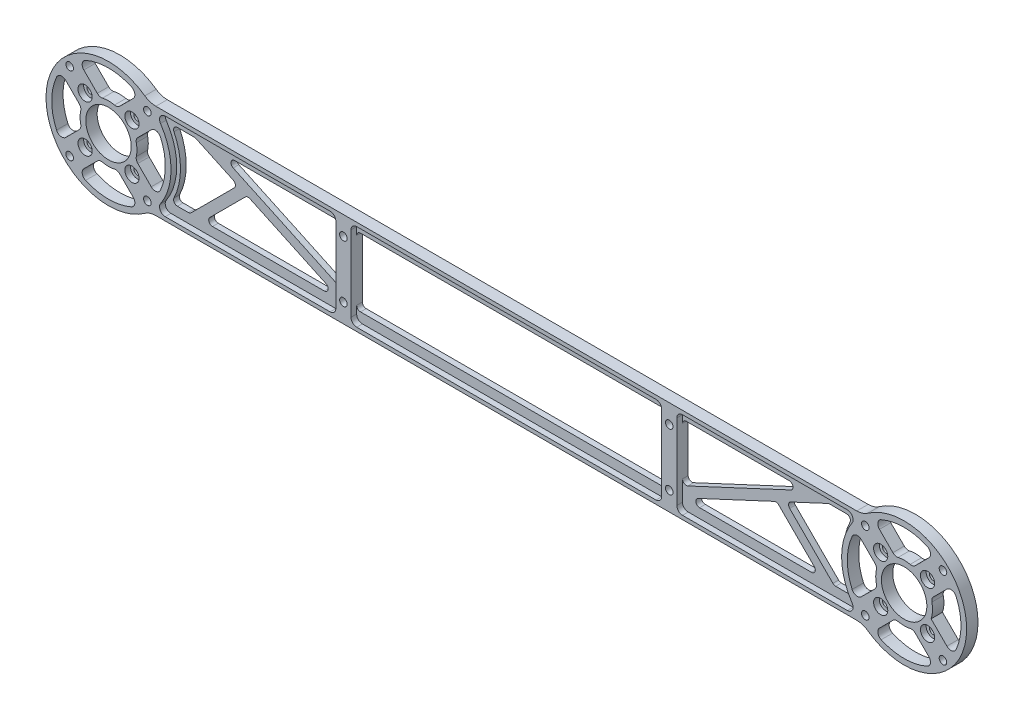
SolidWorks part; units mm, degrees
material "6061 合金"
ref_plane "前视基准面" through (0, 0, 0) normal (0, 0, 1) x (1, 0, 0)
ref_plane "上视基准面" through (0, 0, 0) normal (0, 1, 0) x (1, 0, 0)
ref_plane "右视基准面" through (0, 0, 0) normal (1, 0, 0) x (0, 0, -1)
sketch "草图1" plane through (0, 0, 0) normal (0, 0, 1) x (1, 0, 0)
  line L0 (0, 45.7031) -> (0, -72.9118) construction
  line L1 (-42.6422, 0) -> (420, 0) construction
  line L2 (0, 0) -> (-20.5061, 20.5061) construction
  line L3 (21.5407, 25) -> (398.4593, 25)
  line L4 (21.5407, -25) -> (398.4593, -25)
  line L5 (210, 25) -> (210, -95.809) construction
  line L7 (30.0167, 18) -> (120, 18)
  line L8 (30.0167, 18) -> (30.0167, -18) construction
  line L9 (30.0167, -18) -> (120, -18)
  line L10 (120, 18) -> (120, -18)
  line L11 (30.0167, 18) -> (120, -18) construction
  line L12 (30.0167, -18) -> (120, 18) construction
  line L13 (300, 18) -> (389.9833, 18)
  line L14 (300, 18) -> (300, -18)
  line L15 (300, -18) -> (389.9833, -18)
  line L16 (389.9833, 18) -> (389.9833, -18) construction
  line L17 (300, 18) -> (389.9833, -18) construction
  line L18 (300, -18) -> (389.9833, 18) construction
  line L19 (128, 18) -> (292, 18)
  line L20 (128, 18) -> (128, -18)
  line L21 (128, -18) -> (292, -18)
  line L22 (292, 18) -> (292, -18)
  line L23 (128, 18) -> (292, -18) construction
  line L24 (128, -18) -> (292, 18) construction
  circle A0 centre (0, 0) radius 29 construction
  circle A1 centre (-20.5061, 20.5061) radius 2
  circle A5 centre (20.5061, 20.5061) radius 2
  circle A6 centre (20.5061, -20.5061) radius 2
  circle A7 centre (-20.5061, -20.5061) radius 2
  circle A8 centre (0, 0) radius 12
  arc A9 (21.5407, 25) -> (21.5407, -25) centre (0, 0) ccw
  circle A10 centre (440.5061, 20.5061) radius 2
  arc A11 (398.4593, -25) -> (398.4593, 25) centre (420, 0) ccw
  circle A12 centre (420, 0) radius 12
  circle A13 centre (440.5061, -20.5061) radius 2
  circle A14 centre (399.4939, -20.5061) radius 2
  circle A15 centre (399.4939, 20.5061) radius 2
  arc A17 (389.9833, 18) -> (389.9833, -18) centre (420, 0) ccw
  arc A18 (30.0167, -18) -> (30.0167, 18) centre (0, 0) ccw
  circle A19 centre (-12.3744, 12.3744) radius 2
  circle A20 centre (12.3744, 12.3744) radius 2
  circle A21 centre (12.3744, -12.3744) radius 2
  circle A22 centre (-12.3744, -12.3744) radius 2
  circle A23 centre (407.6256, 12.3744) radius 2
  circle A24 centre (432.3744, 12.3744) radius 2
  circle A25 centre (407.6256, -12.3744) radius 2
  circle A26 centre (432.3744, -12.3744) radius 2
  point P6 (344.9917, 0)
  point P18 (0, 0)
  point P31 (75.0083, 0)
  point P42 (210, 0)
  point P58 (0, 0)
  point P60 (420, 0)
  point P65 (420, 0)
  dimension "D1" = 17
  dimension "D3" = 4
  dimension "D5" = 24
  dimension "D6" = 4
  dimension "D8" = 420
  dimension "D11" = 35
  dimension "D14" = 58
  dimension "D15" = 4
  dimension "D17" = 17.5
  dimension "D2" = 45
  dimension "D9" = 50
  dimension "D10" = 7
  dimension "D12" = 8
  dimension "D13" = 120
  dimension "D7" = 2
  dimension "D18" = 2
  dimension "D4" = 4
  dimension "D16" = 4
extrude "凸台-拉伸1" add sketch "草图1" along normal blind 6
fillet "圆角1" [suppressed] radius 3
sketch "草图2" plane through (0, 0, 6) normal (0, 0, 1) x (1, 0, 0)
  line L0 (210, 25) -> (210, -72.3198) construction
  line L1 (398.4593, 25) -> (21.5407, 25) construction
  line L2 (124, -22.0435) -> (124, 29.2031) construction
  line L3 (128, 18) -> (128, -18) construction
  line L4 (120, 0) -> (300, 0) construction
  line L5 (120, -18) -> (120, 18) construction
  line L6 (300, 18) -> (300, -18) construction
  circle A0 centre (124, 15) radius 2
  circle A1 centre (124, -15) radius 2
  circle A2 centre (296, 15) radius 2
  circle A3 centre (296, -15) radius 2
  dimension "D1" = 4
  dimension "D3" = 30
  dimension "D2" = 4
extrude "切除-拉伸1" cut sketch "草图2" against normal through all
sketch "草图3" plane through (0, 0, 6) normal (0, 0, 1) x (1, 0, 0)
  line L0 (210, -25) -> (210, 69.7704) construction
  line L1 (21.5407, -25) -> (398.4593, -25) construction
  line L2 (398.4593, 25) -> (21.5407, 25) construction
  line L3 (66, 25) -> (74, 25)
  line L4 (66, 25) -> (66, 45)
  line L5 (66, 45) -> (74, 45)
  line L6 (74, 25) -> (74, 45)
  line L7 (0, 0) -> (420, 0) construction
  line L16 (354, 25) -> (346, 25)
  line L17 (354, 25) -> (354, 45)
  line L18 (354, 45) -> (346, 45)
  line L19 (346, 25) -> (346, 45)
  line L20 (70, 45) -> (70, -45) construction
  line L21 (350, 45) -> (350, -45) construction
  circle A1 centre (350, 40) radius 1.6
  circle A2 centre (70, 40) radius 1.6
  point P31 (70, 45)
  point P32 (350, 45)
  dimension "D4" = 3.2
  dimension "D5" = 5
  dimension "D1" = 8
  dimension "D2" = 20
  dimension "D3" = 280
extrude "凸台-拉伸2" [suppressed] add sketch "草图3" against normal up to surface (6 mm away)
fillet "圆角2" [suppressed] radius 3
sketch "草图4" [suppressed] plane through (0, 0, 6) normal (0, 0, 1) x (1, 0, 0)
  line L0 (60, 40) -> (60, -25) construction
  line L1 (21.5407, -25) -> (378.4593, -25) construction
  line L2 (340, 40) -> (340, -25) construction
  line L3 (303, -18) -> (368.3772, -18) construction
  circle A0 centre (60, -21.5) radius 1.5
  circle A1 centre (340, -21.5) radius 1.5
  dimension "D1" = 3
  dimension "D2" = 3.5
extrude "切除-拉伸2" [suppressed] cut sketch "草图4" against normal through all
sketch "草图5" plane through (0, 0, 6) normal (0, 0, 1) x (1, 0, 0)
  line L0 (54.6288, 18) -> (120, -12.4831)
  line L1 (120, 18) -> (30.0167, 18) construction
  line L2 (120, -18) -> (120, 18) construction
  line L3 (120, -12.4831) -> (120, -18)
  line L4 (120, -18) -> (70.2636, 5.1925)
  line L5 (65.4412, 7.4412) -> (40, -18)
  line L6 (30.0167, -18) -> (120, -18) construction
  line L7 (40, -18) -> (47.0711, -18)
  line L8 (47.0711, -18) -> (70.2636, 5.1925)
  line L10 (42.7978, 18) -> (54.6288, 18)
  line L11 (65.4412, 7.4412) -> (42.7978, 18)
  dimension "D1" = 5
  dimension "D2" = 5
  dimension "D3" = 25
  dimension "D4" = 45
  dimension "D5" = 80
extrude "凸台-拉伸3" add sketch "草图5" against normal up to surface (6 mm away) up to face at (126, -15, 0)
ref_plane "基准面1" through (210, 0, 0) normal (-1, 0, 0) x (0, 0, 1)
mirror "镜向1" about plane through (210, 0, 0) normal (-1, 0, 0) of "凸台-拉伸3"
fillet "圆角3" radius 2 25 edges at (349.7364, 5.1925, 3) (300, -18, 3) (372.9289, -18, 3) (354.5588, 7.4412, 3) (380, -18, 3) (389.9833, -18, 3) (389.9833, 18, 3) (365.3712, 18, 3) (300, -12.4831, 3) (300, 18, 3) (292, -18, 3) (292, 18, 3) (128, -18, 3) (128, 18, 3) (42.7978, 18, 3) (30.0167, 18, 3) (30.0167, -18, 3) (40, -18, 3) (47.0711, -18, 3) (120, 18, 3) (120, -12.4831, 3) (120, -18, 3) (70.2636, 5.1925, 3) (65.4412, 7.4412, 3) (54.6288, 18, 3)
sketch "草图6" plane through (0, 0, 6) normal (0, 0, 1) x (1, 0, 0)
  line L0 (120, -9.3437) -> (120, 16) construction
  line L2 (120, 23) -> (120, -23)
  line L4 (128, 23) -> (128, -23)
  line L6 (398.4593, 23) -> (21.5407, 23)
  line L7 (396.3357, 23) -> (300, 23)
  line L8 (292, 23) -> (292, -23)
  line L9 (21.5407, -23) -> (398.4593, -23)
  line L10 (23.6643, -23) -> (120, -23)
  line L12 (300, 23) -> (300, -23)
  line L13 (128, 16) -> (128, -16) construction
  line L14 (292, -16) -> (292, 16) construction
  line L15 (300, 16) -> (300, -9.3437) construction
  line L16 (120, 23) -> (23.6643, 23)
  line L17 (128, -23) -> (292, -23)
  line L18 (300, -23) -> (396.3357, -23)
  line L19 (292, 23) -> (128, 23)
  circle A6 centre (0, 0) radius 33
  arc A7 (23.6643, -23) -> (23.6643, 23) centre (0, 0) ccw
  circle A9 centre (420, 0) radius 33
  arc A10 (396.3357, 23) -> (396.3357, -23) centre (420, 0) ccw
  dimension "D1" = 2
  dimension "D2" = 2
  dimension "D3" = 21
  dimension "D4" = 21
extrude "切除-拉伸3" cut sketch "草图6" against normal blind 3
sketch "草图7" plane through (0, 0, 6) normal (0, 0, 1) x (1, 0, 0)
  line L0 (-15.8963, 25.4422) -> (-4.699, 14.245)
  line L1 (15.8963, 25.4422) -> (4.699, 14.245)
  line L2 (0, 0) -> (0, 39.0557) construction
  line L19 (-12.3744, 12.3744) -> (0, 0) construction
  line L20 (-15.026, 9.7227) -> (-10.712, 5.4087) construction
  line L21 (-9.7227, 15.026) -> (-5.4087, 10.712) construction
  line L22 (9.7227, 15.026) -> (5.4087, 10.712) construction
  line L23 (15.026, 9.7227) -> (10.712, 5.4087) construction
  line L24 (15.026, -9.7227) -> (10.712, -5.4087) construction
  line L25 (9.7227, -15.026) -> (5.4087, -10.712) construction
  line L26 (-9.7227, -15.026) -> (-5.4087, -10.712) construction
  line L27 (-15.026, -9.7227) -> (-10.712, -5.4087) construction
  line L28 (429.7227, 15.026) -> (425.4087, 10.712) construction
  line L29 (435.026, 9.7227) -> (430.712, 5.4087) construction
  line L30 (404.974, 9.7227) -> (409.288, 5.4087) construction
  line L31 (410.2773, 15.026) -> (414.5913, 10.712) construction
  line L32 (410.2773, -15.026) -> (414.5913, -10.712) construction
  line L33 (404.974, -9.7227) -> (409.288, -5.4087) construction
  line L34 (435.026, -9.7227) -> (430.712, -5.4087) construction
  line L35 (429.7227, -15.026) -> (425.4087, -10.712) construction
  line L36 (25.4422, 15.8963) -> (14.245, 4.699)
  line L37 (25.4422, -15.8963) -> (14.245, -4.699)
  line L38 (15.8963, -25.4422) -> (4.699, -14.245)
  line L39 (-15.8963, -25.4422) -> (-4.699, -14.245)
  line L40 (-25.4422, -15.8963) -> (-14.245, -4.699)
  line L41 (-25.4422, 15.8963) -> (-14.245, 4.699)
  line L42 (445.4422, 15.8963) -> (434.245, 4.699)
  line L43 (445.4422, -15.8963) -> (434.245, -4.699)
  line L46 (435.8963, -25.4422) -> (424.699, -14.245)
  line L47 (404.1037, -25.4422) -> (415.301, -14.245)
  line L48 (394.5578, -15.8963) -> (405.755, -4.699)
  line L49 (394.5578, 15.8963) -> (405.755, 4.699)
  line L50 (404.1037, 25.4422) -> (415.301, 14.245)
  line L51 (435.8963, 25.4422) -> (424.699, 14.245)
  circle A2 centre (0, 0) radius 12 construction
  arc A18 (-9.7227, 15.026) -> (-15.026, 9.7227) centre (-12.3744, 12.3744) ccw construction
  circle A27 centre (420, 0) radius 12 construction
  arc A28 (-5.4087, 10.712) -> (-10.712, 5.4087) centre (0, 0) ccw construction
  arc A29 (10.712, 5.4087) -> (5.4087, 10.712) centre (0, 0) ccw construction
  arc A30 (15.026, 9.7227) -> (9.7227, 15.026) centre (12.3744, 12.3744) ccw construction
  arc A31 (5.4087, -10.712) -> (10.712, -5.4087) centre (0, 0) ccw construction
  arc A32 (9.7227, -15.026) -> (15.026, -9.7227) centre (12.3744, -12.3744) ccw construction
  arc A33 (-10.712, -5.4087) -> (-5.4087, -10.712) centre (0, 0) ccw construction
  arc A34 (-15.026, -9.7227) -> (-9.7227, -15.026) centre (-12.3744, -12.3744) ccw construction
  arc A35 (430.712, 5.4087) -> (425.4087, 10.712) centre (420, 0) ccw construction
  arc A36 (435.026, 9.7227) -> (429.7227, 15.026) centre (432.3744, 12.3744) ccw construction
  arc A37 (414.5913, 10.712) -> (409.288, 5.4087) centre (420, 0) ccw construction
  arc A38 (410.2773, 15.026) -> (404.974, 9.7227) centre (407.6256, 12.3744) ccw construction
  arc A39 (409.288, -5.4087) -> (414.5913, -10.712) centre (420, 0) ccw construction
  arc A40 (404.974, -9.7227) -> (410.2773, -15.026) centre (407.6256, -12.3744) ccw construction
  arc A41 (425.4087, -10.712) -> (430.712, -5.4087) centre (420, 0) ccw construction
  arc A42 (429.7227, -15.026) -> (435.026, -9.7227) centre (432.3744, -12.3744) ccw construction
  arc A43 (4.699, 14.245) -> (-4.699, 14.245) centre (0, 0) ccw
  arc A44 (15.8963, 25.4422) -> (-15.8963, 25.4422) centre (0, 0) ccw
  arc A46 (14.245, -4.699) -> (14.245, 4.699) centre (0, 0) ccw
  arc A47 (25.4422, -15.8963) -> (25.4422, 15.8963) centre (0, 0) ccw
  arc A48 (-4.699, -14.245) -> (4.699, -14.245) centre (0, 0) ccw
  arc A49 (-15.8963, -25.4422) -> (15.8963, -25.4422) centre (0, 0) ccw
  arc A50 (-14.245, 4.699) -> (-14.245, -4.699) centre (0, 0) ccw
  arc A51 (-25.4422, 15.8963) -> (-25.4422, -15.8963) centre (0, 0) ccw
  arc A52 (434.245, -4.699) -> (434.245, 4.699) centre (420, 0) ccw
  arc A53 (445.4422, -15.8963) -> (445.4422, 15.8963) centre (420, 0) ccw
  arc A54 (415.301, -14.245) -> (424.699, -14.245) centre (420, 0) ccw
  arc A55 (404.1037, -25.4422) -> (435.8963, -25.4422) centre (420, 0) ccw
  arc A56 (405.755, 4.699) -> (405.755, -4.699) centre (420, 0) ccw
  arc A57 (394.5578, 15.8963) -> (394.5578, -15.8963) centre (420, 0) ccw
  arc A58 (424.699, 14.245) -> (415.301, 14.245) centre (420, 0) ccw
  arc A59 (435.8963, 25.4422) -> (404.1037, 25.4422) centre (420, 0) ccw
  point P27 (0, 0)
  point P28 (0, 0)
  point P70 (0, 0)
  dimension "D1" = 3
  dimension "D2" = 30
  dimension "D6" = 7.5
  dimension "D3" = 3
  dimension "D8" = 2
  dimension "D5" = 2
  dimension "D7" = 4
  dimension "D4" = 4
extrude "切除-拉伸4" cut sketch "草图7" against normal through all
fillet "圆角5" radius 3 12 edges at (396.3357, 23, 4.5) (23.6643, -23, 4.5) (300, -23, 4.5) (292, -23, 4.5) (128, -23, 4.5) (120, -23, 4.5) (120, 23, 4.5) (128, 23, 4.5) (300, 23, 4.5) (292, 23, 4.5) (396.3357, -23, 4.5) (23.6643, 23, 4.5)
fillet "圆角7" radius 3 31 edges at (405.755, -4.699, 3) (405.755, 4.699, 3) (394.5578, 15.8963, 3) (394.5578, -15.8963, 3) (435.8963, -25.4422, 3) (404.1037, -25.4422, 3) (415.301, -14.245, 3) (424.699, -14.245, 3) (445.4422, -15.8963, 3) (434.245, 4.699, 3) (445.4422, 15.8963, 3) (415.301, 14.245, 3) (424.699, 14.245, 3) (435.8963, 25.4422, 3) (404.1037, 25.4422, 3) (-14.245, 4.699, 3) (-14.245, -4.699, 3) (-4.699, -14.245, 3) (4.699, -14.245, 3) (15.8963, -25.4422, 3) (-15.8963, -25.4422, 3) (-25.4422, -15.8963, 3) (-25.4422, 15.8963, 3) (14.245, 4.699, 3) (14.245, -4.699, 3) (25.4422, -15.8963, 3) (25.4422, 15.8963, 3) (4.699, 14.245, 3) (-4.699, 14.245, 3) (15.8963, 25.4422, 3) (-15.8963, 25.4422, 3)
sketch "草图9" plane through (0, 0, 6) normal (0, 0, 1) x (1, 0, 0)
  circle A0 centre (-12.3744, 12.3744) radius 3.75
  circle A1 centre (12.3744, 12.3744) radius 3.75
  circle A2 centre (12.3744, -12.3744) radius 3.75
  circle A3 centre (-12.3744, -12.3744) radius 3.75
  circle A4 centre (407.6256, 12.3744) radius 3.75
  circle A5 centre (432.3744, 12.3744) radius 3.75
  circle A6 centre (432.3744, -12.3744) radius 3.75
  circle A7 centre (407.6256, -12.3744) radius 3.75
  dimension "D1" = 7.5
extrude "切除-拉伸5" cut sketch "草图9" against normal blind 3
fillet "圆角8" radius 10 4 edges at (398.4593, 25, 3) (398.4593, -25, 3) (21.5407, -25, 3) (21.5407, 25, 3)
